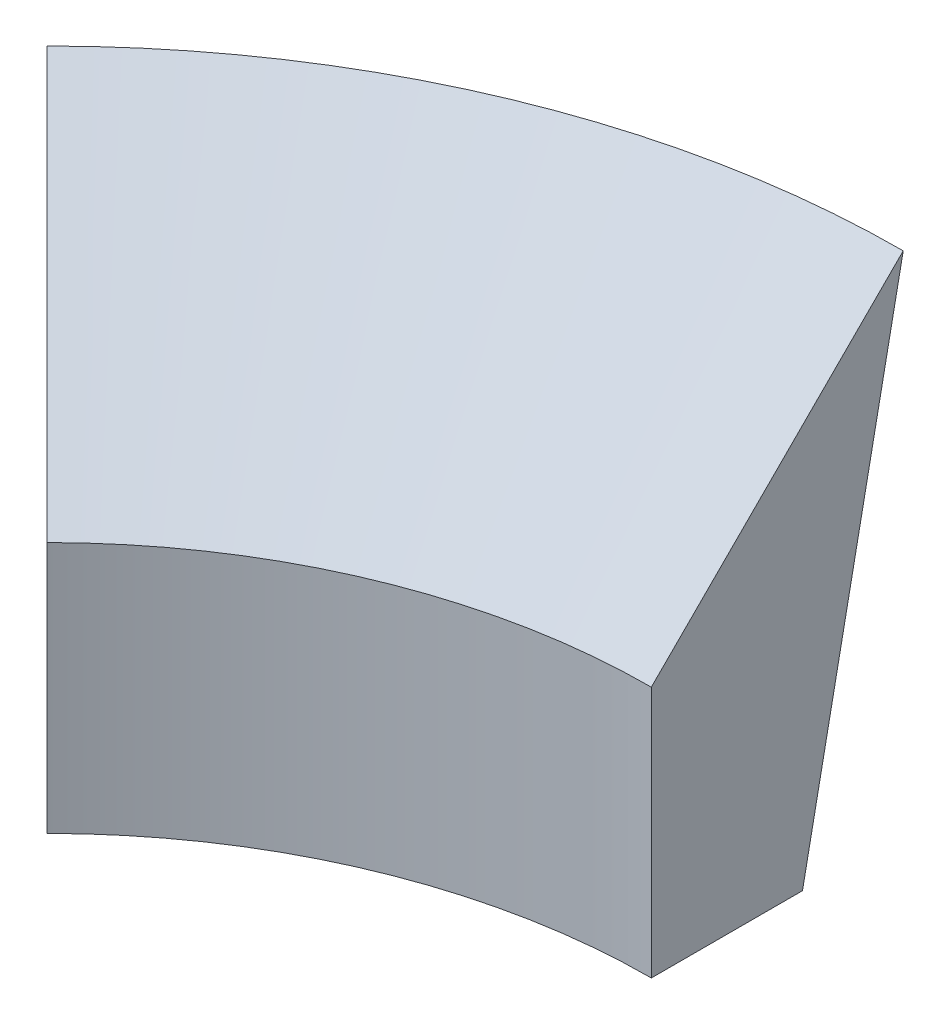
SolidWorks part; units mm, degrees
ref_plane "前基準面" through (0, 0, 0) normal (0, 0, 1) x (1, 0, 0)
ref_plane "上基準面" through (0, 0, 0) normal (0, 1, 0) x (1, 0, 0)
ref_plane "右基準面" through (0, 0, 0) normal (1, 0, 0) x (0, 0, -1)
sketch "草圖1" plane through (0, 0, 0) normal (0, 0, 1) x (1, 0, 0)
  line L0 (-120, 0) -> (-120, -40)
  line L1 (-150, -50) -> (-170, 50)
  line L2 (-170, 50) -> (-120, 0)
  line L3 (0, 0) -> (0, -14.5903) construction
  line L4 (0, -40) -> (0, -50)
  line L5 (-150, -50) -> (0, -50)
  line L9 (-120, -40) -> (0, -40)
  line L10 (-120, -40) -> (-120, -50)
  dimension "D1" = 120
  dimension "D2" = 50
  dimension "D3" = 45
  dimension "D4" = 100
  dimension "D5" = 30
  dimension "D6" = 10
revolve "旋轉2" add sketch "草圖1" angle 360 about L3
sketch "草圖2" plane through (0, 0, 0) normal (0, 1, 0) x (1, 0, 0)
  line L0 (0, 0) -> (0, 170)
  line L9 (0, 0) -> (-120.2082, 120.2082)
  circle A0 centre (0, 0) radius 170 construction
  circle A1 centre (0, 0) radius 170 construction
  arc A2 (-120.2082, 120.2082) -> (0, 170) centre (0, 0) cw
  arc A3 (-120.2082, 120.2082) -> (0, 170) centre (0, 0) ccw
  dimension "D1" = 45
extrude "除料-伸長1" cut sketch "草圖2" against normal through all both and the other way through all contours L9 A3 L0
